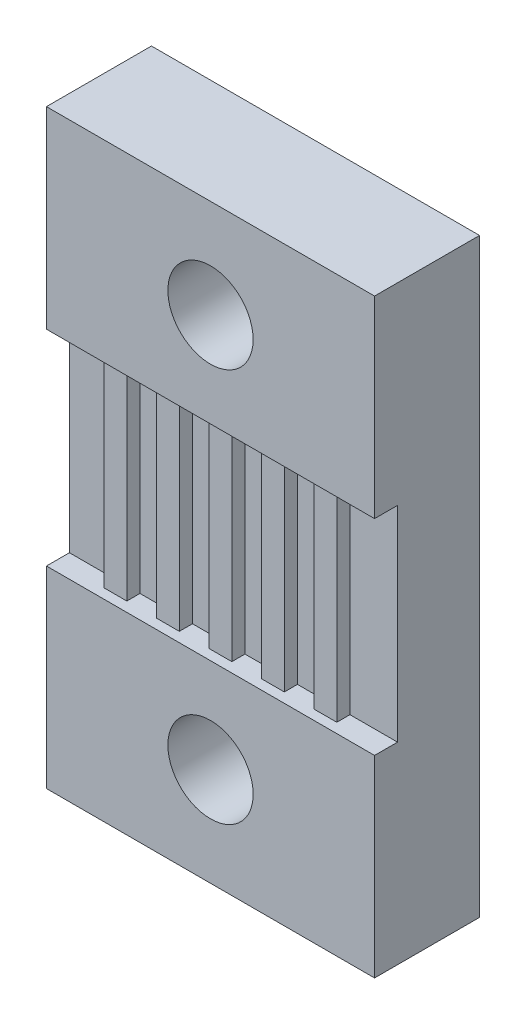
SolidWorks part; units mm, degrees
ref_plane "Front Plane" through (0, 0, 0) normal (0, 0, 1) x (1, 0, 0)
ref_plane "Top Plane" through (0, 0, 0) normal (0, 1, 0) x (1, 0, 0)
ref_plane "Right Plane" through (0, 0, 0) normal (1, 0, 0) x (0, 0, -1)
sketch "Sketch1" plane through (0, 0, 0) normal (0, 0, 1) x (1, 0, 0)
  line L0 (-6.35, 0) -> (6.35, 0) construction
  line L1 (-6.35, -11.43) -> (6.35, -11.43)
  line L2 (-6.35, -11.43) -> (-6.35, 11.43)
  line L3 (-6.35, 11.43) -> (6.35, 11.43)
  line L4 (6.35, -11.43) -> (6.35, 11.43)
  line L5 (-6.35, -11.43) -> (6.35, 11.43) construction
  line L6 (-6.35, 11.43) -> (6.35, -11.43) construction
  circle A0 centre (0, 7.62) radius 1.65
  circle A1 centre (0, -7.62) radius 1.65
  point P0 (0, 0)
  dimension "D3" = 3.3
  dimension "D1" = 22.86
  dimension "D2" = 12.7
  dimension "D4" = 3.81
extrude "Boss-Extrude1" add sketch "Sketch1" along normal blind 3.175
sketch "Sketch2" plane through (0, 0, 3.175) normal (0, 0, 1) x (1, 0, 0)
  line L0 (-6.35, 0) -> (6.35, 0) construction
  line L1 (-6.35, 11.43) -> (-6.35, -11.43) construction
  line L2 (6.35, -11.43) -> (6.35, 11.43) construction
  line L3 (-6.35, -3.9688) -> (6.35, -3.9688)
  line L4 (-6.35, 11.43) -> (6.35, 11.43)
  line L5 (-6.35, 11.43) -> (-6.35, 3.9688)
  line L6 (-6.35, 3.9688) -> (6.35, 3.9688)
  line L7 (6.35, 11.43) -> (6.35, 3.9688)
  line L8 (6.35, -11.43) -> (6.35, -3.9688)
  line L9 (-6.35, -11.43) -> (6.35, -11.43)
  line L10 (-6.35, -11.43) -> (-6.35, -3.9688)
  circle A0 centre (0, -7.62) radius 1.65 construction
  circle A1 centre (0, 7.62) radius 1.65 construction
  circle A2 centre (0, -7.62) radius 1.65
  circle A3 centre (0, 7.62) radius 1.65
  dimension "D1" = 7.9375
extrude "Boss-Extrude2" add sketch "Sketch2" along normal blind 0.889
sketch "Sketch3" plane through (0, 3.9688, 0) normal (0, -1, 0) x (1, 0, 0)
  line L0 (-6.35, 3.175) -> (6.35, 3.175) construction
  line L1 (-0.4445, 3.175) -> (-0.4445, 3.683)
  line L2 (-0.4445, 3.683) -> (0.4445, 3.683)
  line L3 (-0.4445, 3.175) -> (0.4445, 3.175)
  line L6 (0.4445, 3.683) -> (0.4445, 3.175)
  line L7 (0, 3.175) -> (0, 3.683) construction
  point P11 (0, 3.175)
  dimension "D1" = 0.508
  dimension "D5" = 0.889
extrude "Boss-Extrude3" add sketch "Sketch3" along normal up to next
pattern_linear "LPattern1" count 3 spacing 2.032 along (1, 0, 0) count 3 spacing 2.032 along (-1, 0, 0) of "Boss-Extrude3"
